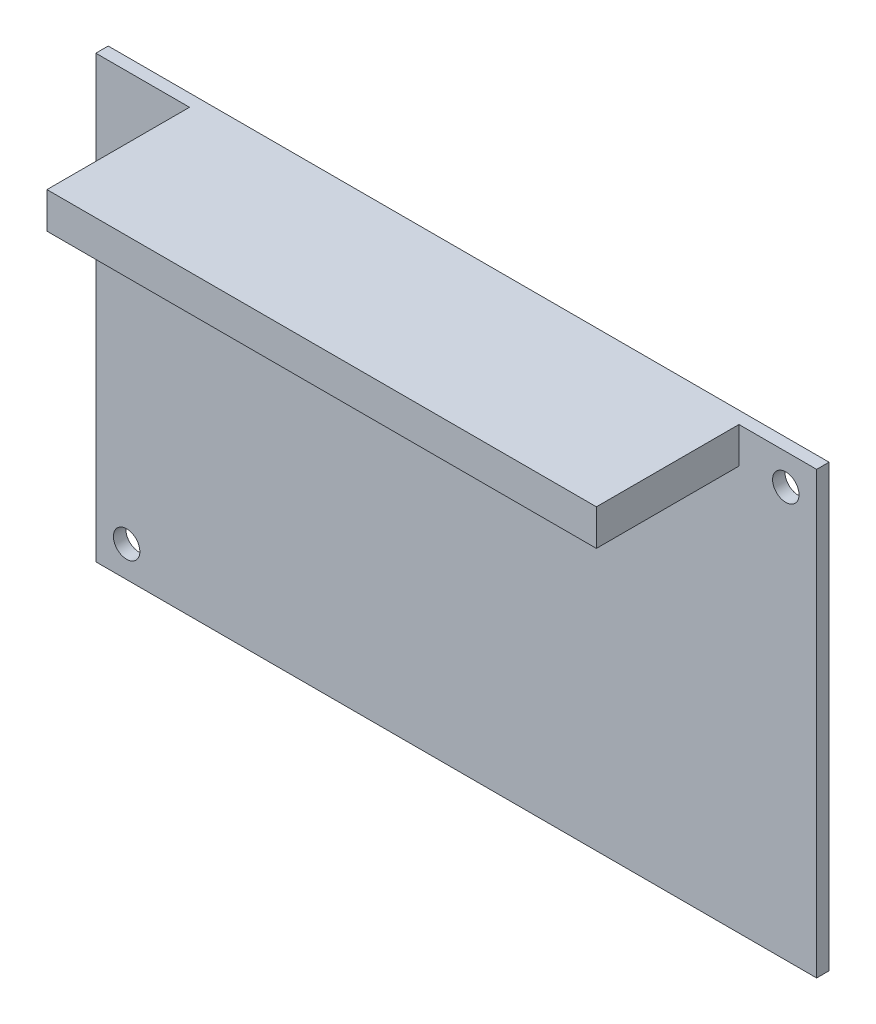
SolidWorks part; units mm, degrees
ref_plane "Ön Düzlem" through (0, 0, 0) normal (0, 0, 1) x (1, 0, 0)
ref_plane "Üst Düzlem" through (0, 0, 0) normal (0, 1, 0) x (1, 0, 0)
ref_plane "Sağ Düzlem" through (0, 0, 0) normal (1, 0, 0) x (0, 0, -1)
sketch "Çizim1" plane through (0, 0, 0) normal (0, 0, 1) x (1, 0, 0)
  line L1 (0, 0) -> (90, 0)
  line L2 (0, 0) -> (0, -55)
  line L3 (0, -55) -> (90, -55)
  line L4 (90, 0) -> (90, -55)
  circle A0 centre (86.15, -3.85) radius 1.65
  circle A1 centre (3.85, -51.15) radius 1.65
  dimension "D3" = 3.3
  dimension "D4" = 3.3
  dimension "D5" = 3.85
  dimension "D6" = 3.85
  dimension "D7" = 3.85
  dimension "D8" = 3.85
  dimension "D1" = 90
  dimension "D2" = 55
extrude "Yükseklik-Ekstrüzyon1" add sketch "Çizim1" along normal blind 1.55
sketch "Çizim2" plane through (0, 0, 1.55) normal (0, 0, 1) x (1, 0, 0)
  line L0 (90, 0) -> (0, 0) construction
  line L1 (11.7, 0) -> (80.3, 0)
  line L2 (11.7, 0) -> (11.7, -4.5)
  line L3 (11.7, -4.5) -> (80.3, -4.5)
  line L4 (80.3, 0) -> (80.3, -4.5)
  line L5 (0, 0) -> (0, -55) construction
  dimension "D1" = 11.7
  dimension "D2" = 68.6
  dimension "D3" = 4.5
extrude "Yükseklik-Ekstrüzyon2" add sketch "Çizim2" along normal blind 17.8
